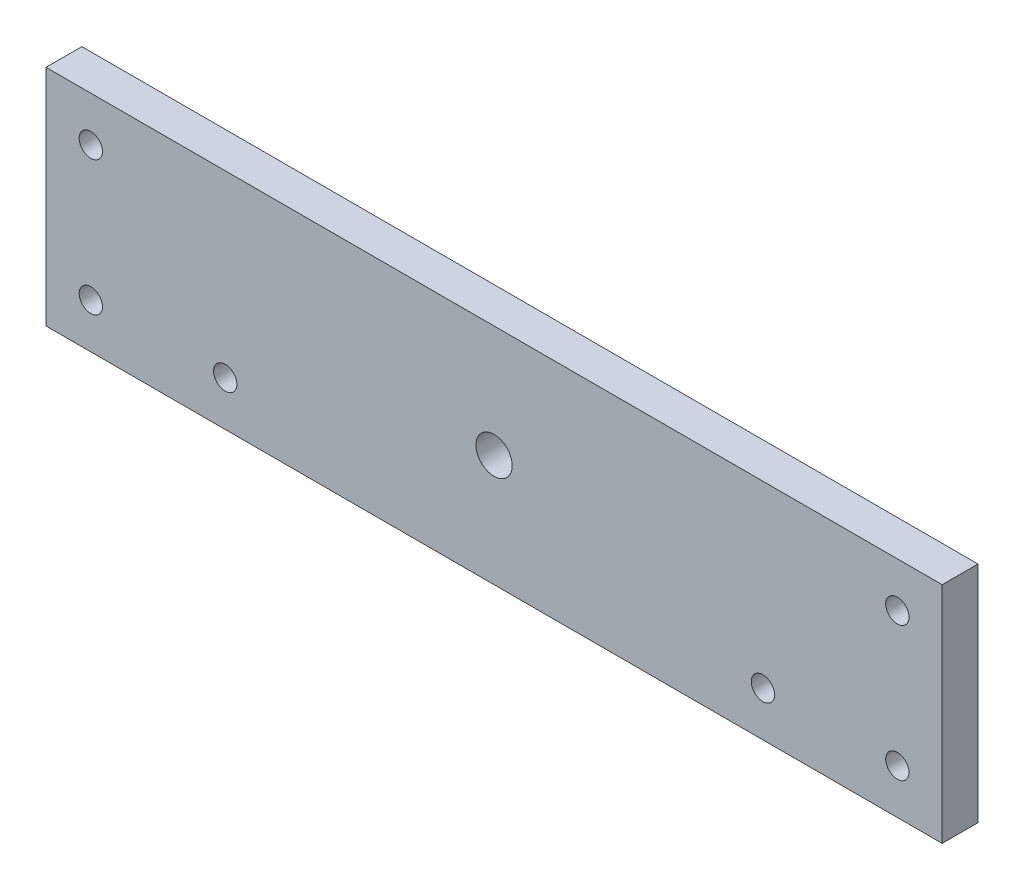
SolidWorks part; units mm, degrees
ref_plane "Ön Düzlem" through (0, 0, 0) normal (0, 0, 1) x (1, 0, 0)
ref_plane "Üst Düzlem" through (0, 0, 0) normal (0, 1, 0) x (1, 0, 0)
ref_plane "Sağ Düzlem" through (0, 0, 0) normal (1, 0, 0) x (0, 0, -1)
sketch "Çizim1" plane through (0, 0, 0) normal (0, 0, 1) x (1, 0, 0)
  line L1 (-88.1446, 49.1848) -> (111.8554, 49.1848)
  line L2 (-88.1446, 49.1848) -> (-88.1446, -0.8152)
  line L3 (-88.1446, -0.8152) -> (111.8554, -0.8152)
  line L4 (111.8554, 49.1848) -> (111.8554, -0.8152)
  circle A3 centre (-78.1446, 39.1848) radius 4.0251
  circle A4 centre (101.8554, 39.1848) radius 4.0251
  circle A5 centre (101.8554, 9.1848) radius 4.0251
  circle A6 centre (-78.1446, 9.1848) radius 4.0251
  dimension "D3" = 10
  dimension "D4" = 10
  dimension "D5" = 2
  dimension "D6" = 2
  dimension "D1" = 200
  dimension "D2" = 50
extrude "Yükseklik-Ekstrüzyon1" add sketch "Çizim1" along normal blind 8 contours L2 L1 L4 L3
hole_wizard "M5 Helisarmal için Zıvana matkabı1" positions "Çizim3" profile "Çizim4" hole size "M5x0.8" standard "ANSI Metric" end condition up to next
sketch "Çizim3" plane through (0, 0, 0) normal (0, 0, -1) x (-1, 0, 0)
  point P0 (-101.8554, 39.1848)
  point P3 (-101.8554, 9.1848)
  point P6 (78.1446, 9.1848)
  point P9 (78.1446, 39.1848)
sketch "Çizim4" plane through (101.8554, 39.1848, 0) normal (1, 0, 0) x (0, 1, 0)
  line L0 (0, 0) -> (0, 8)
  line L1 (0, 8) -> (2.6, 8)
  line L2 (2.6, 8) -> (2.6, 0)
  line L5 (2.6, 0) -> (0, 0)
  line L11 (0, -6.35) -> (0, 107.95) construction
  dimension "Thru Hole Dia." = 5.2
  dimension "Thru Hole Depth" = 8
sketch "Çizim6" plane through (0, 0, 0) normal (0, 0, -1) x (-1, 0, 0)
  line L0 (88.1446, -0.8152) -> (-111.8554, -0.8152) construction
  line L1 (-111.8554, 49.1848) -> (-111.8554, -0.8152) construction
  line L2 (88.1446, 49.1848) -> (88.1446, -0.8152) construction
  circle A0 centre (-71.8554, 9.1848) radius 3.103
  circle A1 centre (48.1446, 9.1848) radius 2.2755
  dimension "D1" = 10
  dimension "D2" = 40
  dimension "D3" = 10
  dimension "D4" = 40
hole_wizard "M5 Helisarmal için Zıvana matkabı2" positions "3B Çizim2" profile "Çizim7" hole size "M5x0.8" standard "ANSI Metric" end condition up to next
sketch3d "3B Çizim2"
  point P0 (71.8554, 9.1848, 0)
  point P3 (-48.1446, 9.1848, 0)
sketch "Çizim7" plane through (71.8554, 9.1848, 0) normal (1, 0, 0) x (0, 1, 0)
  line L0 (0, 0) -> (0, 8)
  line L1 (0, 8) -> (2.6, 8)
  line L2 (2.6, 8) -> (2.6, 0)
  line L5 (2.6, 0) -> (0, 0)
  line L11 (0, -6.35) -> (0, 107.95) construction
  dimension "Thru Hole Dia." = 5.2
  dimension "Thru Hole Depth" = 8
sketch "Çizim8" plane through (0, 0, 0) normal (0, 0, -1) x (-1, 0, 0)
  line L0 (-11.8554, 49.1848) -> (-11.8554, -0.8152)
  line L1 (88.1446, 49.1848) -> (-111.8554, 49.1848) construction
  line L2 (88.1446, -0.8152) -> (-111.8554, -0.8152) construction
  circle A0 centre (-11.8554, 24.1848) radius 4.05
  dimension "D1" = 8.1
extrude "Kes-Ekstrüzyon1" cut sketch "Çizim8" against normal blind 10 contours L0 A0 | L0 A0
